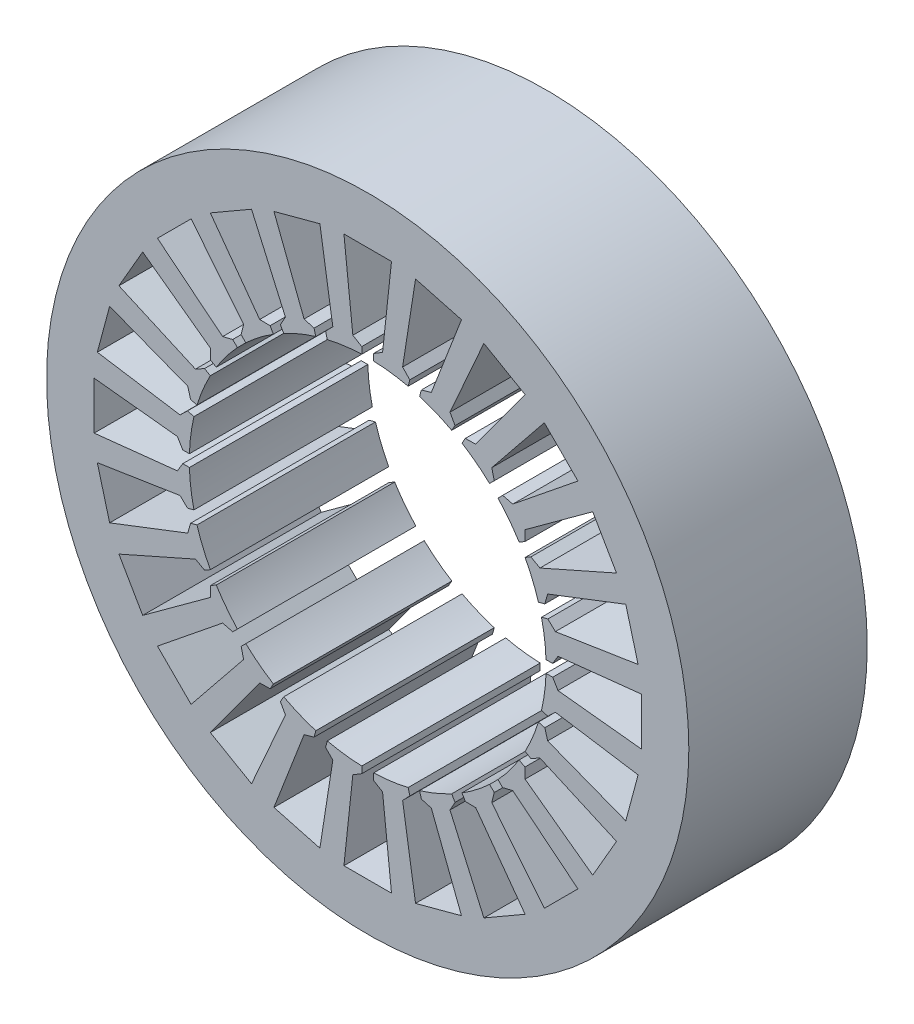
SolidWorks part; units mm, degrees
ref_plane "Спереди" through (0, 0, 0) normal (0, 0, 1) x (1, 0, 0)
ref_plane "Сверху" through (0, 0, 0) normal (0, 1, 0) x (1, 0, 0)
ref_plane "Справа" through (0, 0, 0) normal (1, 0, 0) x (0, 0, -1)
sketch "Эскиз1" plane through (0, 0, 0) normal (0, 0, 1) x (1, 0, 0)
  circle A0 centre (0, 0) radius 54
  circle A1 centre (0, 0) radius 30
extrude "Stator_stack" add sketch "Эскиз1" along normal blind 30 from offset 15
sketch "Эскиз2" plane through (0, 0, 0) normal (0, 0, 1) x (1, 0, 0)
  line L0 (28.9828, -1) -> (31.1, -1)
  line L1 (31.1, -1) -> (32, -2.5)
  line L2 (32, -2.5) -> (39.5, -3.3036)
  line L3 (39.5, -3.3036) -> (46, -4)
  line L4 (46, -4) -> (46, 4)
  line L5 (46, 4) -> (39.5, 3.3036)
  line L6 (39.5, 3.3036) -> (32, 2.5)
  line L7 (32, 2.5) -> (31.1, 1)
  line L8 (31.1, 1) -> (28.9828, 1)
  line L9 (28.9828, 1) -> (28.9828, -1)
  line L10 (28.254, 6.5354) -> (30.2991, 7.0833)
  line L11 (30.2991, 7.0833) -> (31.5567, 5.8674)
  line L12 (31.5567, 5.8674) -> (39.0091, 7.0323)
  line L13 (39.0091, 7.0323) -> (45.4679, 8.042)
  line L14 (45.4679, 8.042) -> (43.3973, 15.7694)
  line L15 (43.3973, 15.7694) -> (37.299, 13.4144)
  line L16 (37.299, 13.4144) -> (30.2626, 10.697)
  line L17 (30.2626, 10.697) -> (29.7815, 9.0152)
  line L18 (29.7815, 9.0152) -> (27.7364, 8.4672)
  line L19 (27.7364, 8.4672) -> (28.254, 6.5354)
  line L20 (25.5998, 13.6254) -> (27.4334, 14.684)
  line L21 (27.4334, 14.684) -> (28.9628, 13.8349)
  line L22 (28.9628, 13.8349) -> (35.8598, 16.889)
  line L23 (35.8598, 16.889) -> (41.8372, 19.5359)
  line L24 (41.8372, 19.5359) -> (37.8372, 26.4641)
  line L25 (37.8372, 26.4641) -> (32.5562, 22.611)
  line L26 (32.5562, 22.611) -> (26.4628, 18.1651)
  line L27 (26.4628, 18.1651) -> (26.4334, 16.416)
  line L28 (26.4334, 16.416) -> (24.5998, 15.3574)
  line L29 (24.5998, 15.3574) -> (25.5998, 13.6254)
  line L30 (21.201, 19.7868) -> (22.6981, 21.2839)
  line L31 (22.6981, 21.2839) -> (24.3952, 20.8597)
  line L32 (24.3952, 20.8597) -> (30.2667, 25.5947)
  line L33 (30.2667, 25.5947) -> (35.3553, 29.6985)
  line L34 (35.3553, 29.6985) -> (29.6985, 35.3553)
  line L35 (29.6985, 35.3553) -> (25.5947, 30.2667)
  line L36 (25.5947, 30.2667) -> (20.8597, 24.3952)
  line L37 (20.8597, 24.3952) -> (21.2839, 22.6981)
  line L38 (21.2839, 22.6981) -> (19.7868, 21.201)
  line L39 (19.7868, 21.201) -> (21.201, 19.7868)
  line L40 (15.3574, 24.5998) -> (16.416, 26.4334)
  line L41 (16.416, 26.4334) -> (18.1651, 26.4628)
  line L42 (18.1651, 26.4628) -> (22.611, 32.5562)
  line L43 (22.611, 32.5562) -> (26.4641, 37.8372)
  line L44 (26.4641, 37.8372) -> (19.5359, 41.8372)
  line L45 (19.5359, 41.8372) -> (16.889, 35.8598)
  line L46 (16.889, 35.8598) -> (13.8349, 28.9628)
  line L47 (13.8349, 28.9628) -> (14.684, 27.4334)
  line L48 (14.684, 27.4334) -> (13.6254, 25.5998)
  line L49 (13.6254, 25.5998) -> (15.3574, 24.5998)
  line L50 (8.4672, 27.7364) -> (9.0152, 29.7815)
  line L51 (9.0152, 29.7815) -> (10.697, 30.2626)
  line L52 (10.697, 30.2626) -> (13.4144, 37.299)
  line L53 (13.4144, 37.299) -> (15.7694, 43.3973)
  line L54 (15.7694, 43.3973) -> (8.042, 45.4679)
  line L55 (8.042, 45.4679) -> (7.0323, 39.0091)
  line L56 (7.0323, 39.0091) -> (5.8674, 31.5567)
  line L57 (5.8674, 31.5567) -> (7.0833, 30.2991)
  line L58 (7.0833, 30.2991) -> (6.5354, 28.254)
  line L59 (6.5354, 28.254) -> (8.4672, 27.7364)
  line L60 (1, 28.9828) -> (1, 31.1)
  line L61 (1, 31.1) -> (2.5, 32)
  line L62 (2.5, 32) -> (3.3036, 39.5)
  line L63 (3.3036, 39.5) -> (4, 46)
  line L64 (4, 46) -> (-4, 46)
  line L65 (-4, 46) -> (-3.3036, 39.5)
  line L66 (-3.3036, 39.5) -> (-2.5, 32)
  line L67 (-2.5, 32) -> (-1, 31.1)
  line L68 (-1, 31.1) -> (-1, 28.9828)
  line L69 (-1, 28.9828) -> (1, 28.9828)
  line L70 (-6.5354, 28.254) -> (-7.0833, 30.2991)
  line L71 (-7.0833, 30.2991) -> (-5.8674, 31.5567)
  line L72 (-5.8674, 31.5567) -> (-7.0323, 39.0091)
  line L73 (-7.0323, 39.0091) -> (-8.042, 45.4679)
  line L74 (-8.042, 45.4679) -> (-15.7694, 43.3973)
  line L75 (-15.7694, 43.3973) -> (-13.4144, 37.299)
  line L76 (-13.4144, 37.299) -> (-10.697, 30.2626)
  line L77 (-10.697, 30.2626) -> (-9.0152, 29.7815)
  line L78 (-9.0152, 29.7815) -> (-8.4672, 27.7364)
  line L79 (-8.4672, 27.7364) -> (-6.5354, 28.254)
  line L80 (-13.6254, 25.5998) -> (-14.684, 27.4334)
  line L81 (-14.684, 27.4334) -> (-13.8349, 28.9628)
  line L82 (-13.8349, 28.9628) -> (-16.889, 35.8598)
  line L83 (-16.889, 35.8598) -> (-19.5359, 41.8372)
  line L84 (-19.5359, 41.8372) -> (-26.4641, 37.8372)
  line L85 (-26.4641, 37.8372) -> (-22.611, 32.5562)
  line L86 (-22.611, 32.5562) -> (-18.1651, 26.4628)
  line L87 (-18.1651, 26.4628) -> (-16.416, 26.4334)
  line L88 (-16.416, 26.4334) -> (-15.3574, 24.5998)
  line L89 (-15.3574, 24.5998) -> (-13.6254, 25.5998)
  line L90 (-19.7868, 21.201) -> (-21.2839, 22.6981)
  line L91 (-21.2839, 22.6981) -> (-20.8597, 24.3952)
  line L92 (-20.8597, 24.3952) -> (-25.5947, 30.2667)
  line L93 (-25.5947, 30.2667) -> (-29.6985, 35.3553)
  line L94 (-29.6985, 35.3553) -> (-35.3553, 29.6985)
  line L95 (-35.3553, 29.6985) -> (-30.2667, 25.5947)
  line L96 (-30.2667, 25.5947) -> (-24.3952, 20.8597)
  line L97 (-24.3952, 20.8597) -> (-22.6981, 21.2839)
  line L98 (-22.6981, 21.2839) -> (-21.201, 19.7868)
  line L99 (-21.201, 19.7868) -> (-19.7868, 21.201)
  line L100 (-24.5998, 15.3574) -> (-26.4334, 16.416)
  line L101 (-26.4334, 16.416) -> (-26.4628, 18.1651)
  line L102 (-26.4628, 18.1651) -> (-32.5562, 22.611)
  line L103 (-32.5562, 22.611) -> (-37.8372, 26.4641)
  line L104 (-37.8372, 26.4641) -> (-41.8372, 19.5359)
  line L105 (-41.8372, 19.5359) -> (-35.8598, 16.889)
  line L106 (-35.8598, 16.889) -> (-28.9628, 13.8349)
  line L107 (-28.9628, 13.8349) -> (-27.4334, 14.684)
  line L108 (-27.4334, 14.684) -> (-25.5998, 13.6254)
  line L109 (-25.5998, 13.6254) -> (-24.5998, 15.3574)
  line L110 (-27.7364, 8.4672) -> (-29.7815, 9.0152)
  line L111 (-29.7815, 9.0152) -> (-30.2626, 10.697)
  line L112 (-30.2626, 10.697) -> (-37.299, 13.4144)
  line L113 (-37.299, 13.4144) -> (-43.3973, 15.7694)
  line L114 (-43.3973, 15.7694) -> (-45.4679, 8.042)
  line L115 (-45.4679, 8.042) -> (-39.0091, 7.0323)
  line L116 (-39.0091, 7.0323) -> (-31.5567, 5.8674)
  line L117 (-31.5567, 5.8674) -> (-30.2991, 7.0833)
  line L118 (-30.2991, 7.0833) -> (-28.254, 6.5354)
  line L119 (-28.254, 6.5354) -> (-27.7364, 8.4672)
  line L120 (-28.9828, 1) -> (-31.1, 1)
  line L121 (-31.1, 1) -> (-32, 2.5)
  line L122 (-32, 2.5) -> (-39.5, 3.3036)
  line L123 (-39.5, 3.3036) -> (-46, 4)
  line L124 (-46, 4) -> (-46, -4)
  line L125 (-46, -4) -> (-39.5, -3.3036)
  line L126 (-39.5, -3.3036) -> (-32, -2.5)
  line L127 (-32, -2.5) -> (-31.1, -1)
  line L128 (-31.1, -1) -> (-28.9828, -1)
  line L129 (-28.9828, -1) -> (-28.9828, 1)
  line L130 (-28.254, -6.5354) -> (-30.2991, -7.0833)
  line L131 (-30.2991, -7.0833) -> (-31.5567, -5.8674)
  line L132 (-31.5567, -5.8674) -> (-39.0091, -7.0323)
  line L133 (-39.0091, -7.0323) -> (-45.4679, -8.042)
  line L134 (-45.4679, -8.042) -> (-43.3973, -15.7694)
  line L135 (-43.3973, -15.7694) -> (-37.299, -13.4144)
  line L136 (-37.299, -13.4144) -> (-30.2626, -10.697)
  line L137 (-30.2626, -10.697) -> (-29.7815, -9.0152)
  line L138 (-29.7815, -9.0152) -> (-27.7364, -8.4672)
  line L139 (-27.7364, -8.4672) -> (-28.254, -6.5354)
  line L140 (-25.5998, -13.6254) -> (-27.4334, -14.684)
  line L141 (-27.4334, -14.684) -> (-28.9628, -13.8349)
  line L142 (-28.9628, -13.8349) -> (-35.8598, -16.889)
  line L143 (-35.8598, -16.889) -> (-41.8372, -19.5359)
  line L144 (-41.8372, -19.5359) -> (-37.8372, -26.4641)
  line L145 (-37.8372, -26.4641) -> (-32.5562, -22.611)
  line L146 (-32.5562, -22.611) -> (-26.4628, -18.1651)
  line L147 (-26.4628, -18.1651) -> (-26.4334, -16.416)
  line L148 (-26.4334, -16.416) -> (-24.5998, -15.3574)
  line L149 (-24.5998, -15.3574) -> (-25.5998, -13.6254)
  line L150 (-21.201, -19.7868) -> (-22.6981, -21.2839)
  line L151 (-22.6981, -21.2839) -> (-24.3952, -20.8597)
  line L152 (-24.3952, -20.8597) -> (-30.2667, -25.5947)
  line L153 (-30.2667, -25.5947) -> (-35.3553, -29.6985)
  line L154 (-35.3553, -29.6985) -> (-29.6985, -35.3553)
  line L155 (-29.6985, -35.3553) -> (-25.5947, -30.2667)
  line L156 (-25.5947, -30.2667) -> (-20.8597, -24.3952)
  line L157 (-20.8597, -24.3952) -> (-21.2839, -22.6981)
  line L158 (-21.2839, -22.6981) -> (-19.7868, -21.201)
  line L159 (-19.7868, -21.201) -> (-21.201, -19.7868)
  line L160 (-15.3574, -24.5998) -> (-16.416, -26.4334)
  line L161 (-16.416, -26.4334) -> (-18.1651, -26.4628)
  line L162 (-18.1651, -26.4628) -> (-22.611, -32.5562)
  line L163 (-22.611, -32.5562) -> (-26.4641, -37.8372)
  line L164 (-26.4641, -37.8372) -> (-19.5359, -41.8372)
  line L165 (-19.5359, -41.8372) -> (-16.889, -35.8598)
  line L166 (-16.889, -35.8598) -> (-13.8349, -28.9628)
  line L167 (-13.8349, -28.9628) -> (-14.684, -27.4334)
  line L168 (-14.684, -27.4334) -> (-13.6254, -25.5998)
  line L169 (-13.6254, -25.5998) -> (-15.3574, -24.5998)
  line L170 (-8.4672, -27.7364) -> (-9.0152, -29.7815)
  line L171 (-9.0152, -29.7815) -> (-10.697, -30.2626)
  line L172 (-10.697, -30.2626) -> (-13.4144, -37.299)
  line L173 (-13.4144, -37.299) -> (-15.7694, -43.3973)
  line L174 (-15.7694, -43.3973) -> (-8.042, -45.4679)
  line L175 (-8.042, -45.4679) -> (-7.0323, -39.0091)
  line L176 (-7.0323, -39.0091) -> (-5.8674, -31.5567)
  line L177 (-5.8674, -31.5567) -> (-7.0833, -30.2991)
  line L178 (-7.0833, -30.2991) -> (-6.5354, -28.254)
  line L179 (-6.5354, -28.254) -> (-8.4672, -27.7364)
  line L180 (-1, -28.9828) -> (-1, -31.1)
  line L181 (-1, -31.1) -> (-2.5, -32)
  line L182 (-2.5, -32) -> (-3.3036, -39.5)
  line L183 (-3.3036, -39.5) -> (-4, -46)
  line L184 (-4, -46) -> (4, -46)
  line L185 (4, -46) -> (3.3036, -39.5)
  line L186 (3.3036, -39.5) -> (2.5, -32)
  line L187 (2.5, -32) -> (1, -31.1)
  line L188 (1, -31.1) -> (1, -28.9828)
  line L189 (1, -28.9828) -> (-1, -28.9828)
  line L190 (6.5354, -28.254) -> (7.0833, -30.2991)
  line L191 (7.0833, -30.2991) -> (5.8674, -31.5567)
  line L192 (5.8674, -31.5567) -> (7.0323, -39.0091)
  line L193 (7.0323, -39.0091) -> (8.042, -45.4679)
  line L194 (8.042, -45.4679) -> (15.7694, -43.3973)
  line L195 (15.7694, -43.3973) -> (13.4144, -37.299)
  line L196 (13.4144, -37.299) -> (10.697, -30.2626)
  line L197 (10.697, -30.2626) -> (9.0152, -29.7815)
  line L198 (9.0152, -29.7815) -> (8.4672, -27.7364)
  line L199 (8.4672, -27.7364) -> (6.5354, -28.254)
  line L200 (13.6254, -25.5998) -> (14.684, -27.4334)
  line L201 (14.684, -27.4334) -> (13.8349, -28.9628)
  line L202 (13.8349, -28.9628) -> (16.889, -35.8598)
  line L203 (16.889, -35.8598) -> (19.5359, -41.8372)
  line L204 (19.5359, -41.8372) -> (26.4641, -37.8372)
  line L205 (26.4641, -37.8372) -> (22.611, -32.5562)
  line L206 (22.611, -32.5562) -> (18.1651, -26.4628)
  line L207 (18.1651, -26.4628) -> (16.416, -26.4334)
  line L208 (16.416, -26.4334) -> (15.3574, -24.5998)
  line L209 (15.3574, -24.5998) -> (13.6254, -25.5998)
  line L210 (19.7868, -21.201) -> (21.2839, -22.6981)
  line L211 (21.2839, -22.6981) -> (20.8597, -24.3952)
  line L212 (20.8597, -24.3952) -> (25.5947, -30.2667)
  line L213 (25.5947, -30.2667) -> (29.6985, -35.3553)
  line L214 (29.6985, -35.3553) -> (35.3553, -29.6985)
  line L215 (35.3553, -29.6985) -> (30.2667, -25.5947)
  line L216 (30.2667, -25.5947) -> (24.3952, -20.8597)
  line L217 (24.3952, -20.8597) -> (22.6981, -21.2839)
  line L218 (22.6981, -21.2839) -> (21.201, -19.7868)
  line L219 (21.201, -19.7868) -> (19.7868, -21.201)
  line L220 (24.5998, -15.3574) -> (26.4334, -16.416)
  line L221 (26.4334, -16.416) -> (26.4628, -18.1651)
  line L222 (26.4628, -18.1651) -> (32.5562, -22.611)
  line L223 (32.5562, -22.611) -> (37.8372, -26.4641)
  line L224 (37.8372, -26.4641) -> (41.8372, -19.5359)
  line L225 (41.8372, -19.5359) -> (35.8598, -16.889)
  line L226 (35.8598, -16.889) -> (28.9628, -13.8349)
  line L227 (28.9628, -13.8349) -> (27.4334, -14.684)
  line L228 (27.4334, -14.684) -> (25.5998, -13.6254)
  line L229 (25.5998, -13.6254) -> (24.5998, -15.3574)
  line L230 (27.7364, -8.4672) -> (29.7815, -9.0152)
  line L231 (29.7815, -9.0152) -> (30.2626, -10.697)
  line L232 (30.2626, -10.697) -> (37.299, -13.4144)
  line L233 (37.299, -13.4144) -> (43.3973, -15.7694)
  line L234 (43.3973, -15.7694) -> (45.4679, -8.042)
  line L235 (45.4679, -8.042) -> (39.0091, -7.0323)
  line L236 (39.0091, -7.0323) -> (31.5567, -5.8674)
  line L237 (31.5567, -5.8674) -> (30.2991, -7.0833)
  line L238 (30.2991, -7.0833) -> (28.254, -6.5354)
  line L239 (28.254, -6.5354) -> (27.7364, -8.4672)
extrude "Stator_slots" cut sketch "Эскиз2" against normal mid plane 32
